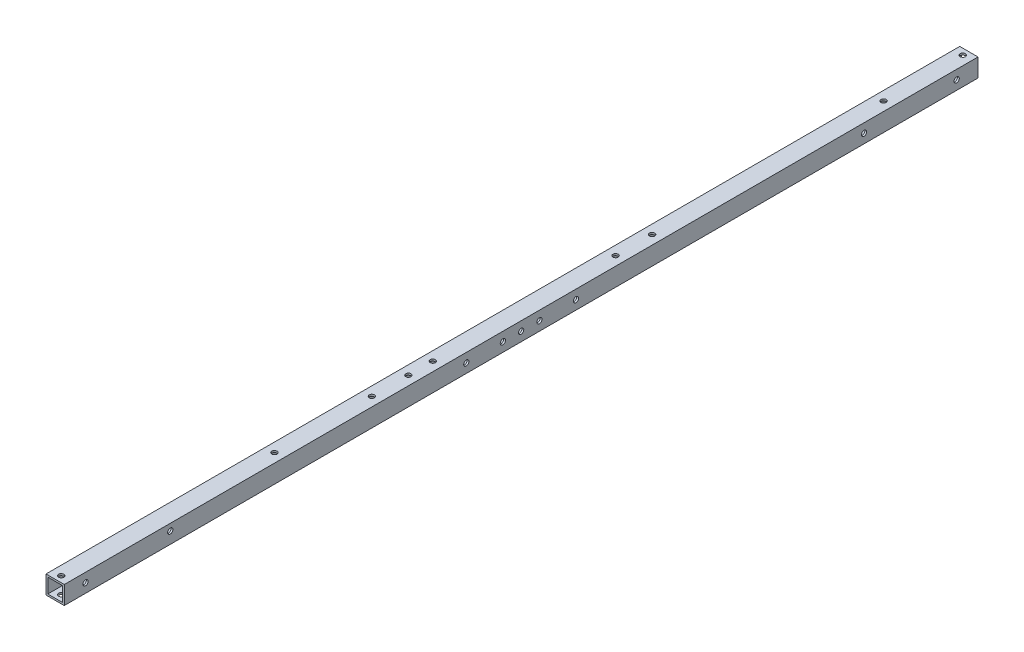
SolidWorks part; units mm, degrees
material "5052-H34"
ref_plane "正面" through (0, 0, 0) normal (0, 0, 1) x (1, 0, 0)
ref_plane "平面" through (0, 0, 0) normal (0, 1, 0) x (1, 0, 0)
ref_plane "右側面" through (0, 0, 0) normal (1, 0, 0) x (0, 0, -1)
sketch "ｽｹｯﾁ1" plane through (0, 0, 0) normal (0, 0, 1) x (1, 0, 0)
  line L1 (-7.5, 7.5) -> (7.5, 7.5)
  line L2 (-7.5, 7.5) -> (-7.5, -7.5)
  line L3 (-7.5, -7.5) -> (7.5, -7.5)
  line L4 (7.5, 7.5) -> (7.5, -7.5)
  line L5 (-7.5, 7.5) -> (7.5, -7.5) construction
  line L6 (-7.5, -7.5) -> (7.5, 7.5) construction
  point P0 (0, 0)
  dimension "D1" = 15
  dimension "D2" = 15
extrude "押し出し-薄板2" add sketch "ｽｹｯﾁ1" along normal blind 750 thin
sketch "ｽｹｯﾁ3" plane through (0, 7.5, 0) normal (0, 1, 0) x (1, 0, 0)
  line L0 (-7.5, -375) -> (7.5, -375) construction
  line L1 (-7.5, -750) -> (-7.5, 0) construction
  line L2 (7.5, -750) -> (7.5, 0) construction
  line L3 (0, -750) -> (0, -745) construction
  line L4 (7.5, -750) -> (-7.5, -750) construction
  line L5 (0, -460) -> (0, -490) construction
  line L9 (7.5, -255) -> (-7.5, -255) construction
  line L10 (0, -255) -> (0, -70) construction
  line L11 (0, -290) -> (0, -260) construction
  circle A0 centre (0, -745) radius 2.15
  circle A1 centre (0, -5) radius 2.15
  circle A2 centre (0, -490) radius 2.15
  circle A3 centre (0, -460) radius 2.15
  circle A4 centre (0, -570) radius 2.15
  circle A5 centre (0, -290) radius 2.15
  circle A6 centre (0, -260) radius 2.15
  circle A9 centre (0, -70) radius 2.15
  circle A10 centre (0, -440) radius 2.15
  point P40 (0, -475)
  point P41 (0, -275)
  dimension "D1" = 4.3
  dimension "D5" = 4.3
  dimension "D7" = 4.3
  dimension "D8" = 130
  dimension "D13" = 4.3
  dimension "D2" = 5
  dimension "D3" = 200
  dimension "D4" = 30
  dimension "D6" = 180
  dimension "D12" = 120
extrude "ｶｯﾄ - 押し出し1" cut sketch "ｽｹｯﾁ3" against normal through all
sketch "ｽｹｯﾁ4" plane through (7.5, 0, 0) normal (1, 0, 0) x (0, 0, -1)
  line L0 (-390, 0) -> (-360, 0) construction
  line L1 (-750, -7.5) -> (-750, 7.5) construction
  line L2 (-750, 0) -> (-732.5, 0) construction
  line L3 (-375, 7.5) -> (-375, -7.5) construction
  line L4 (-750, 7.5) -> (0, 7.5) construction
  line L5 (-750, -7.5) -> (0, -7.5) construction
  line L6 (-750, 0) -> (-420, 0) construction
  line L7 (0, 0) -> (-93.5, 0) construction
  circle A0 centre (-360, 0) radius 2.15
  circle A1 centre (-390, 0) radius 2.15
  circle A2 centre (-375, 0) radius 2.15
  circle A3 centre (-732.5, 0) radius 2.15
  circle A4 centre (-17.5, 0) radius 2.15
  circle A5 centre (-420, 0) radius 2.15
  circle A6 centre (-330, 0) radius 2.15
  circle A9 centre (-663, 2) radius 2.15
  circle A10 centre (-93.5, 0) radius 2.15
  point P3 (-375, 0)
  dimension "D3" = 4.3
  dimension "D4" = 4.3
  dimension "D7" = 4.3
  dimension "D8" = 93.5
  dimension "D13" = 4.3
  dimension "D9" = 4.3
  dimension "D1" = 375
  dimension "D2" = 30
  dimension "D5" = 17.5
  dimension "D6" = 330
  dimension "D11" = 87
  dimension "D12" = 5.5
extrude "ｶｯﾄ - 押し出し2" cut sketch "ｽｹｯﾁ4" against normal through all
